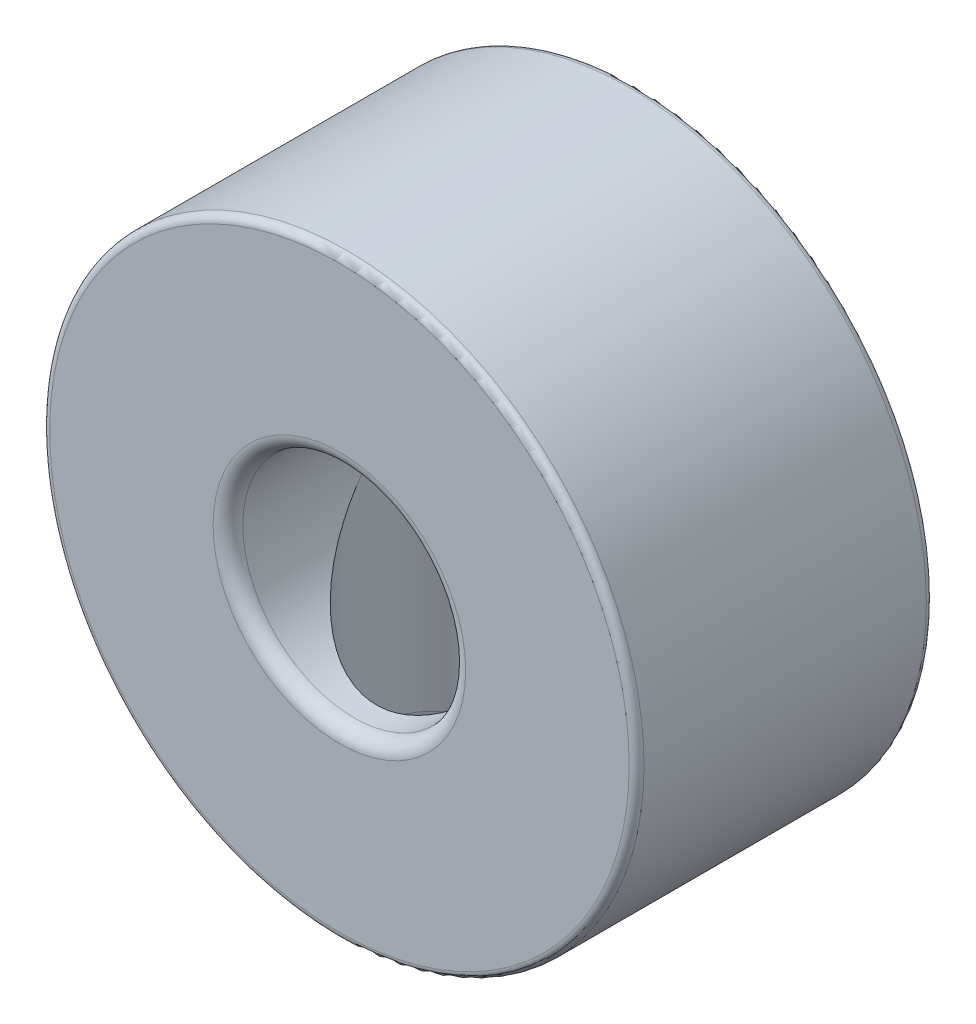
SolidWorks part; units mm, degrees
ref_plane "Alzado" through (0, 0, 0) normal (0, 0, 1) x (1, 0, 0)
ref_plane "Planta" through (0, 0, 0) normal (0, 1, 0) x (1, 0, 0)
ref_plane "Vista lateral" through (0, 0, 0) normal (1, 0, 0) x (0, 0, -1)
sketch "Croquis1" plane through (0, 0, 0) normal (0, 0, 1) x (1, 0, 0)
  circle A0 centre (0, 0) radius 4
  circle A1 centre (0, 0) radius 1.5
  dimension "D1" = 3
  dimension "D2" = 8
extrude "Saliente-Extruir1" add sketch "Croquis1" along normal blind 4
sketch "Croquis2" plane through (0, 0, 0) normal (0, 1, 0) x (1, 0, 0)
  line L1 (4, -2) -> (-0.0024, -2) construction
  line L2 (4, -4) -> (4, 0) construction
  circle A0 centre (-0.0024, -2) radius 1.5
  dimension "D1" = 3
extrude "Cortar-Extruir1" cut sketch "Croquis2" against normal blind 4
fillet "Redondeo1" radius 0.1 1 edges at (4, 0, 4)
fillet "Redondeo2" radius 0.1 1 edges at (4, 0, 0)
fillet "Redondeo3" radius 0.2 1 edges at (1.5, 0, 4)
fillet "Redondeo4" radius 0.2 1 edges at (1.5, 0, 0)
fillet "Redondeo5" radius 0.3 1 edges at (0.2272, -3.9935, 3.4823)
